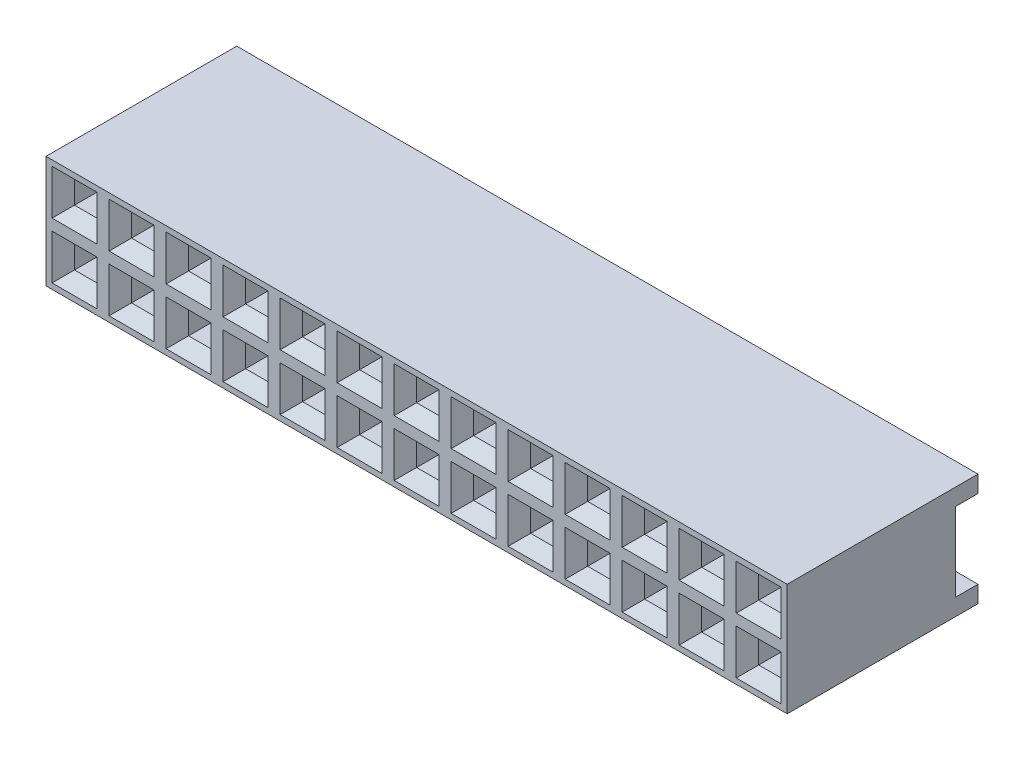
SolidWorks part; units mm, degrees
ref_plane "Ön Düzlem" through (0, 0, 0) normal (0, 0, 1) x (1, 0, 0)
ref_plane "Üst Düzlem" through (0, 0, 0) normal (0, 1, 0) x (1, 0, 0)
ref_plane "Sağ Düzlem" through (0, 0, 0) normal (1, 0, 0) x (0, 0, -1)
sketch "Sketch1" plane through (0, 0, 0) normal (0, 0, 1) x (1, 0, 0)
  line L1 (-68.639, 19.486) -> (-35.619, 19.486)
  line L2 (-68.639, 19.486) -> (-68.639, 14.486)
  line L3 (-68.639, 14.486) -> (-35.619, 14.486)
  line L4 (-35.619, 19.486) -> (-35.619, 14.486)
  dimension "D1" = 33.02
  dimension "D2" = 5
extrude "Boss-Extrude1" add sketch "Sketch1" along normal blind 8.5
sketch "Sketch2" plane through (0, 0, 8.5) normal (0, 0, 1) x (1, 0, 0)
  line L0 (-35.619, 19.486) -> (-68.639, 19.486) construction
  line L1 (-67.869, 17.736) -> (-66.869, 17.736)
  line L2 (-67.869, 17.736) -> (-67.869, 18.736)
  line L3 (-67.869, 18.736) -> (-66.869, 18.736)
  line L4 (-66.869, 17.736) -> (-66.869, 18.736)
  line L5 (-68.639, 19.486) -> (-68.639, 14.486) construction
  line L6 (-65.329, 17.736) -> (-65.329, 18.736)
  line L7 (-65.329, 18.736) -> (-64.329, 18.736)
  line L8 (-64.329, 17.736) -> (-64.329, 18.736)
  line L9 (-65.329, 17.736) -> (-64.329, 17.736)
  line L10 (-62.789, 17.736) -> (-62.789, 18.736)
  line L11 (-62.789, 18.736) -> (-61.789, 18.736)
  line L12 (-61.789, 17.736) -> (-61.789, 18.736)
  line L13 (-62.789, 17.736) -> (-61.789, 17.736)
  line L14 (-60.249, 17.736) -> (-60.249, 18.736)
  line L15 (-60.249, 18.736) -> (-59.249, 18.736)
  line L16 (-59.249, 17.736) -> (-59.249, 18.736)
  line L17 (-60.249, 17.736) -> (-59.249, 17.736)
  line L18 (-57.709, 17.736) -> (-57.709, 18.736)
  line L19 (-57.709, 18.736) -> (-56.709, 18.736)
  line L20 (-56.709, 17.736) -> (-56.709, 18.736)
  line L21 (-57.709, 17.736) -> (-56.709, 17.736)
  line L22 (-55.169, 17.736) -> (-55.169, 18.736)
  line L23 (-55.169, 18.736) -> (-54.169, 18.736)
  line L24 (-54.169, 17.736) -> (-54.169, 18.736)
  line L25 (-55.169, 17.736) -> (-54.169, 17.736)
  line L26 (-52.629, 17.736) -> (-52.629, 18.736)
  line L27 (-52.629, 18.736) -> (-51.629, 18.736)
  line L28 (-51.629, 17.736) -> (-51.629, 18.736)
  line L29 (-52.629, 17.736) -> (-51.629, 17.736)
  line L30 (-50.089, 17.736) -> (-50.089, 18.736)
  line L31 (-50.089, 18.736) -> (-49.089, 18.736)
  line L32 (-49.089, 17.736) -> (-49.089, 18.736)
  line L33 (-50.089, 17.736) -> (-49.089, 17.736)
  line L34 (-47.549, 17.736) -> (-47.549, 18.736)
  line L35 (-47.549, 18.736) -> (-46.549, 18.736)
  line L36 (-46.549, 17.736) -> (-46.549, 18.736)
  line L37 (-47.549, 17.736) -> (-46.549, 17.736)
  line L38 (-45.009, 17.736) -> (-45.009, 18.736)
  line L39 (-45.009, 18.736) -> (-44.009, 18.736)
  line L40 (-44.009, 17.736) -> (-44.009, 18.736)
  line L41 (-45.009, 17.736) -> (-44.009, 17.736)
  line L42 (-42.469, 17.736) -> (-42.469, 18.736)
  line L43 (-42.469, 18.736) -> (-41.469, 18.736)
  line L44 (-41.469, 17.736) -> (-41.469, 18.736)
  line L45 (-42.469, 17.736) -> (-41.469, 17.736)
  line L46 (-39.929, 17.736) -> (-39.929, 18.736)
  line L47 (-39.929, 18.736) -> (-38.929, 18.736)
  line L48 (-38.929, 17.736) -> (-38.929, 18.736)
  line L49 (-39.929, 17.736) -> (-38.929, 17.736)
  line L50 (-37.389, 17.736) -> (-37.389, 18.736)
  line L51 (-37.389, 18.736) -> (-36.389, 18.736)
  line L52 (-36.389, 17.736) -> (-36.389, 18.736)
  line L53 (-37.389, 17.736) -> (-36.389, 17.736)
  line L54 (-65.329, 15.236) -> (-65.329, 16.236)
  line L55 (-65.329, 16.236) -> (-64.329, 16.236)
  line L56 (-64.329, 15.236) -> (-64.329, 16.236)
  line L57 (-65.329, 15.236) -> (-64.329, 15.236)
  line L58 (-62.789, 15.236) -> (-62.789, 16.236)
  line L59 (-62.789, 16.236) -> (-61.789, 16.236)
  line L60 (-61.789, 15.236) -> (-61.789, 16.236)
  line L61 (-62.789, 15.236) -> (-61.789, 15.236)
  line L62 (-60.249, 15.236) -> (-60.249, 16.236)
  line L63 (-60.249, 16.236) -> (-59.249, 16.236)
  line L64 (-59.249, 15.236) -> (-59.249, 16.236)
  line L65 (-60.249, 15.236) -> (-59.249, 15.236)
  line L66 (-57.709, 15.236) -> (-57.709, 16.236)
  line L67 (-57.709, 16.236) -> (-56.709, 16.236)
  line L68 (-56.709, 15.236) -> (-56.709, 16.236)
  line L69 (-57.709, 15.236) -> (-56.709, 15.236)
  line L70 (-55.169, 15.236) -> (-55.169, 16.236)
  line L71 (-55.169, 16.236) -> (-54.169, 16.236)
  line L72 (-54.169, 15.236) -> (-54.169, 16.236)
  line L73 (-55.169, 15.236) -> (-54.169, 15.236)
  line L74 (-52.629, 15.236) -> (-52.629, 16.236)
  line L75 (-52.629, 16.236) -> (-51.629, 16.236)
  line L76 (-51.629, 15.236) -> (-51.629, 16.236)
  line L77 (-52.629, 15.236) -> (-51.629, 15.236)
  line L78 (-50.089, 15.236) -> (-50.089, 16.236)
  line L79 (-50.089, 16.236) -> (-49.089, 16.236)
  line L80 (-49.089, 15.236) -> (-49.089, 16.236)
  line L81 (-50.089, 15.236) -> (-49.089, 15.236)
  line L82 (-47.549, 15.236) -> (-47.549, 16.236)
  line L83 (-47.549, 16.236) -> (-46.549, 16.236)
  line L84 (-46.549, 15.236) -> (-46.549, 16.236)
  line L85 (-47.549, 15.236) -> (-46.549, 15.236)
  line L86 (-45.009, 15.236) -> (-45.009, 16.236)
  line L87 (-45.009, 16.236) -> (-44.009, 16.236)
  line L88 (-44.009, 15.236) -> (-44.009, 16.236)
  line L89 (-45.009, 15.236) -> (-44.009, 15.236)
  line L90 (-42.469, 15.236) -> (-42.469, 16.236)
  line L91 (-42.469, 16.236) -> (-41.469, 16.236)
  line L92 (-41.469, 15.236) -> (-41.469, 16.236)
  line L93 (-42.469, 15.236) -> (-41.469, 15.236)
  line L94 (-39.929, 15.236) -> (-39.929, 16.236)
  line L95 (-39.929, 16.236) -> (-38.929, 16.236)
  line L96 (-38.929, 15.236) -> (-38.929, 16.236)
  line L97 (-39.929, 15.236) -> (-38.929, 15.236)
  line L98 (-37.389, 15.236) -> (-37.389, 16.236)
  line L99 (-37.389, 16.236) -> (-36.389, 16.236)
  line L100 (-36.389, 15.236) -> (-36.389, 16.236)
  line L101 (-37.389, 15.236) -> (-36.389, 15.236)
  line L102 (-67.869, 15.236) -> (-67.869, 16.236)
  line L103 (-67.869, 16.236) -> (-66.869, 16.236)
  line L104 (-66.869, 15.236) -> (-66.869, 16.236)
  line L105 (-67.869, 15.236) -> (-66.869, 15.236)
  dimension "D1" = 1
  dimension "D2" = 1
  dimension "D3" = 0.75
  dimension "D4" = 0.77
  dimension "D5" = 13
  dimension "D6" = 2
extrude "Cut-Extrude1" cut sketch "Sketch2" against normal blind 6
chamfer "Chamfer1" distance 0.5 angle 45 104 edges at (-67.869, 18.236, 8.5) (-67.369, 18.736, 8.5) (-66.869, 18.236, 8.5) (-67.369, 17.736, 8.5) (-37.389, 15.736, 8.5) (-36.889, 15.236, 8.5) (-36.389, 15.736, 8.5) (-36.889, 16.236, 8.5) (-36.889, 17.736, 8.5) (-36.389, 18.236, 8.5) (-36.889, 18.736, 8.5) (-37.389, 18.236, 8.5) (-39.429, 17.736, 8.5) (-39.929, 18.236, 8.5) (-39.429, 18.736, 8.5) (-38.929, 18.236, 8.5) (-39.429, 15.236, 8.5) (-38.929, 15.736, 8.5) (-39.429, 16.236, 8.5) (-39.929, 15.736, 8.5) (-41.969, 15.236, 8.5) (-42.469, 15.736, 8.5) (-41.469, 15.736, 8.5) (-41.969, 16.236, 8.5) (-41.969, 17.736, 8.5) (-42.469, 18.236, 8.5) (-41.969, 18.736, 8.5) (-41.469, 18.236, 8.5) (-47.549, 15.736, 8.5) (-47.049, 15.236, 8.5) (-46.549, 15.736, 8.5) (-47.049, 16.236, 8.5) (-45.009, 15.736, 8.5) (-44.509, 15.236, 8.5) (-44.009, 15.736, 8.5) (-44.509, 16.236, 8.5) (-44.509, 17.736, 8.5) (-44.009, 18.236, 8.5) (-44.509, 18.736, 8.5) (-45.009, 18.236, 8.5) (-46.549, 18.236, 8.5) (-47.049, 17.736, 8.5) (-47.549, 18.236, 8.5) (-47.049, 18.736, 8.5) (-49.589, 15.236, 8.5) (-49.089, 15.736, 8.5) (-50.089, 15.736, 8.5) (-49.589, 16.236, 8.5) (-49.589, 17.736, 8.5) (-49.089, 18.236, 8.5) (-49.589, 18.736, 8.5) (-50.089, 18.236, 8.5) (-52.129, 17.736, 8.5) (-52.629, 18.236, 8.5) (-51.629, 18.236, 8.5) (-52.129, 18.736, 8.5) (-54.669, 17.736, 8.5) (-55.169, 18.236, 8.5) (-54.169, 18.236, 8.5) (-54.669, 18.736, 8.5) (-52.129, 15.236, 8.5) (-51.629, 15.736, 8.5) (-52.129, 16.236, 8.5) (-52.629, 15.736, 8.5) (-54.669, 15.236, 8.5) (-54.169, 15.736, 8.5) (-54.669, 16.236, 8.5) (-55.169, 15.736, 8.5) (-56.709, 15.736, 8.5) (-57.209, 15.236, 8.5) (-57.709, 15.736, 8.5) (-57.209, 16.236, 8.5) (-57.209, 17.736, 8.5) (-56.709, 18.236, 8.5) (-57.209, 18.736, 8.5) (-57.709, 18.236, 8.5) (-59.249, 15.736, 8.5) (-59.749, 15.236, 8.5) (-60.249, 15.736, 8.5) (-59.749, 16.236, 8.5) (-59.749, 17.736, 8.5) (-59.249, 18.236, 8.5) (-59.749, 18.736, 8.5) (-60.249, 18.236, 8.5) (-61.789, 15.736, 8.5) (-62.289, 15.236, 8.5) (-62.789, 15.736, 8.5) (-62.289, 16.236, 8.5) (-65.329, 15.736, 8.5) (-64.829, 15.236, 8.5) (-64.329, 15.736, 8.5) (-64.829, 16.236, 8.5) (-66.869, 15.736, 8.5) (-67.369, 15.236, 8.5) (-67.869, 15.736, 8.5) (-67.369, 16.236, 8.5) (-62.289, 17.736, 8.5) (-61.789, 18.236, 8.5) (-62.289, 18.736, 8.5) (-62.789, 18.236, 8.5) (-64.829, 17.736, 8.5) (-65.329, 18.236, 8.5) (-64.329, 18.236, 8.5) (-64.829, 18.736, 8.5)
sketch "Sketch3" plane through (0, 0, 0) normal (0, 0, -1) x (-1, 0, 0)
  line L1 (68.369, 15.236) -> (66.369, 15.236)
  line L2 (68.369, 15.236) -> (68.369, 15.836)
  line L3 (68.369, 15.836) -> (66.369, 15.836)
  line L4 (66.369, 15.236) -> (66.369, 15.836)
  line L6 (65.829, 15.236) -> (63.829, 15.236)
  line L7 (65.829, 15.236) -> (65.829, 15.836)
  line L8 (65.829, 15.836) -> (63.829, 15.836)
  line L9 (63.829, 15.236) -> (63.829, 15.836)
  line L10 (63.289, 15.236) -> (61.289, 15.236)
  line L11 (63.289, 15.236) -> (63.289, 15.836)
  line L12 (63.289, 15.836) -> (61.289, 15.836)
  line L13 (61.289, 15.236) -> (61.289, 15.836)
  line L14 (60.749, 15.236) -> (58.749, 15.236)
  line L15 (60.749, 15.236) -> (60.749, 15.836)
  line L16 (60.749, 15.836) -> (58.749, 15.836)
  line L17 (58.749, 15.236) -> (58.749, 15.836)
  line L18 (58.209, 15.236) -> (56.209, 15.236)
  line L19 (58.209, 15.236) -> (58.209, 15.836)
  line L20 (58.209, 15.836) -> (56.209, 15.836)
  line L21 (56.209, 15.236) -> (56.209, 15.836)
  line L22 (55.669, 15.236) -> (53.669, 15.236)
  line L23 (55.669, 15.236) -> (55.669, 15.836)
  line L24 (55.669, 15.836) -> (53.669, 15.836)
  line L25 (53.669, 15.236) -> (53.669, 15.836)
  line L26 (53.129, 15.236) -> (51.129, 15.236)
  line L27 (53.129, 15.236) -> (53.129, 15.836)
  line L28 (53.129, 15.836) -> (51.129, 15.836)
  line L29 (51.129, 15.236) -> (51.129, 15.836)
  line L30 (50.589, 15.236) -> (48.589, 15.236)
  line L31 (50.589, 15.236) -> (50.589, 15.836)
  line L32 (50.589, 15.836) -> (48.589, 15.836)
  line L33 (48.589, 15.236) -> (48.589, 15.836)
  line L34 (48.049, 15.236) -> (46.049, 15.236)
  line L35 (48.049, 15.236) -> (48.049, 15.836)
  line L36 (48.049, 15.836) -> (46.049, 15.836)
  line L37 (46.049, 15.236) -> (46.049, 15.836)
  line L38 (45.509, 15.236) -> (43.509, 15.236)
  line L39 (45.509, 15.236) -> (45.509, 15.836)
  line L40 (45.509, 15.836) -> (43.509, 15.836)
  line L41 (43.509, 15.236) -> (43.509, 15.836)
  line L42 (42.969, 15.236) -> (40.969, 15.236)
  line L43 (42.969, 15.236) -> (42.969, 15.836)
  line L44 (42.969, 15.836) -> (40.969, 15.836)
  line L45 (40.969, 15.236) -> (40.969, 15.836)
  line L46 (40.429, 15.236) -> (38.429, 15.236)
  line L47 (40.429, 15.236) -> (40.429, 15.836)
  line L48 (40.429, 15.836) -> (38.429, 15.836)
  line L49 (38.429, 15.236) -> (38.429, 15.836)
  line L50 (37.889, 15.236) -> (35.889, 15.236)
  line L51 (37.889, 15.236) -> (37.889, 15.836)
  line L52 (37.889, 15.836) -> (35.889, 15.836)
  line L53 (35.889, 15.236) -> (35.889, 15.836)
  line L54 (65.829, 18.136) -> (63.829, 18.136)
  line L55 (65.829, 18.136) -> (65.829, 18.736)
  line L56 (65.829, 18.736) -> (63.829, 18.736)
  line L57 (63.829, 18.136) -> (63.829, 18.736)
  line L58 (63.289, 18.136) -> (61.289, 18.136)
  line L59 (63.289, 18.136) -> (63.289, 18.736)
  line L60 (63.289, 18.736) -> (61.289, 18.736)
  line L61 (61.289, 18.136) -> (61.289, 18.736)
  line L62 (60.749, 18.136) -> (58.749, 18.136)
  line L63 (60.749, 18.136) -> (60.749, 18.736)
  line L64 (60.749, 18.736) -> (58.749, 18.736)
  line L65 (58.749, 18.136) -> (58.749, 18.736)
  line L66 (58.209, 18.136) -> (56.209, 18.136)
  line L67 (58.209, 18.136) -> (58.209, 18.736)
  line L68 (58.209, 18.736) -> (56.209, 18.736)
  line L69 (56.209, 18.136) -> (56.209, 18.736)
  line L70 (55.669, 18.136) -> (53.669, 18.136)
  line L71 (55.669, 18.136) -> (55.669, 18.736)
  line L72 (55.669, 18.736) -> (53.669, 18.736)
  line L73 (53.669, 18.136) -> (53.669, 18.736)
  line L74 (53.129, 18.136) -> (51.129, 18.136)
  line L75 (53.129, 18.136) -> (53.129, 18.736)
  line L76 (53.129, 18.736) -> (51.129, 18.736)
  line L77 (51.129, 18.136) -> (51.129, 18.736)
  line L78 (50.589, 18.136) -> (48.589, 18.136)
  line L79 (50.589, 18.136) -> (50.589, 18.736)
  line L80 (50.589, 18.736) -> (48.589, 18.736)
  line L81 (48.589, 18.136) -> (48.589, 18.736)
  line L82 (48.049, 18.136) -> (46.049, 18.136)
  line L83 (48.049, 18.136) -> (48.049, 18.736)
  line L84 (48.049, 18.736) -> (46.049, 18.736)
  line L85 (46.049, 18.136) -> (46.049, 18.736)
  line L86 (45.509, 18.136) -> (43.509, 18.136)
  line L87 (45.509, 18.136) -> (45.509, 18.736)
  line L88 (45.509, 18.736) -> (43.509, 18.736)
  line L89 (43.509, 18.136) -> (43.509, 18.736)
  line L90 (42.969, 18.136) -> (40.969, 18.136)
  line L91 (42.969, 18.136) -> (42.969, 18.736)
  line L92 (42.969, 18.736) -> (40.969, 18.736)
  line L93 (40.969, 18.136) -> (40.969, 18.736)
  line L94 (40.429, 18.136) -> (38.429, 18.136)
  line L95 (40.429, 18.136) -> (40.429, 18.736)
  line L96 (40.429, 18.736) -> (38.429, 18.736)
  line L97 (38.429, 18.136) -> (38.429, 18.736)
  line L98 (37.889, 18.136) -> (35.889, 18.136)
  line L99 (37.889, 18.136) -> (37.889, 18.736)
  line L100 (37.889, 18.736) -> (35.889, 18.736)
  line L101 (35.889, 18.136) -> (35.889, 18.736)
  line L102 (68.369, 18.136) -> (66.369, 18.136)
  line L103 (68.369, 18.136) -> (68.369, 18.736)
  line L104 (68.369, 18.736) -> (66.369, 18.736)
  line L105 (66.369, 18.136) -> (66.369, 18.736)
  line L107 (68.639, 14.486) -> (35.619, 14.486) construction
  dimension "D1" = 2
  dimension "D2" = 0.75
  dimension "D3" = 0.6
  dimension "D4" = 2.3
  dimension "D5" = 13
  dimension "D6" = 2
extrude "Cut-Extrude2" cut sketch "Sketch3" against normal blind 6.5
sketch "Sketch4" plane through (0, 0, 0) normal (0, 0, -1) x (-1, 0, 0)
  line L0 (35.619, 14.486) -> (35.619, 19.486) construction
  line L1 (35.619, 18.736) -> (68.639, 18.736)
  line L2 (35.619, 18.736) -> (35.619, 15.236)
  line L3 (35.619, 15.236) -> (68.639, 15.236)
  line L4 (68.639, 18.736) -> (68.639, 15.236)
  line L5 (68.639, 19.486) -> (68.639, 14.486) construction
  line L6 (35.619, 19.486) -> (68.639, 19.486) construction
  line L7 (68.639, 14.486) -> (35.619, 14.486) construction
  dimension "D1" = 0.75
  dimension "D2" = 0.75
extrude "Cut-Extrude3" cut sketch "Sketch4" against normal blind 1
